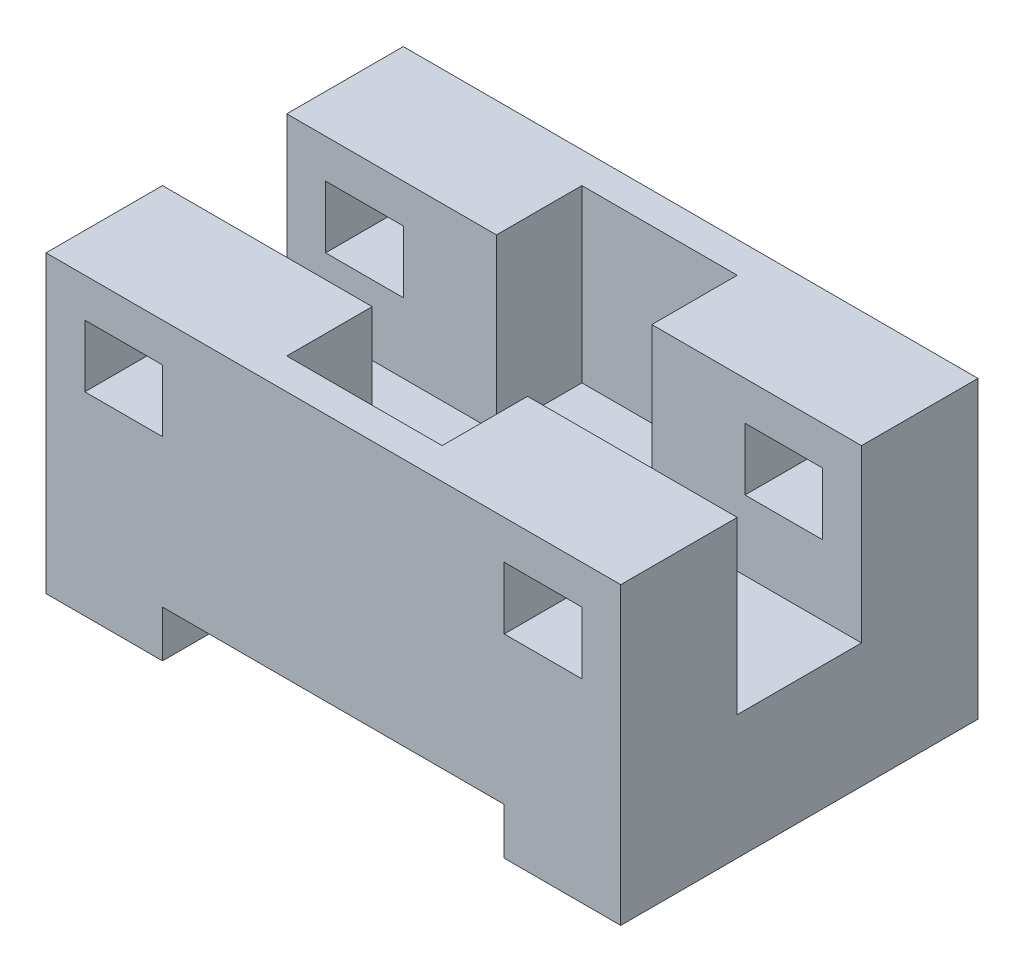
SolidWorks part; units mm, degrees
ref_plane "Alzado" through (0, 0, 0) normal (0, 0, 1) x (1, 0, 0)
ref_plane "Planta" through (0, 0, 0) normal (0, 1, 0) x (1, 0, 0)
ref_plane "Vista lateral" through (0, 0, 0) normal (1, 0, 0) x (0, 0, -1)
sketch "Croquis1" plane through (0, 0, 0) normal (0, 0, 1) x (1, 0, 0)
  line L0 (22, -6) -> (37, -6)
  line L1 (-37, 32) -> (37, 32)
  line L2 (-37, 32) -> (-37, -6)
  line L3 (-37, -6) -> (-22, -6)
  line L4 (37, 32) -> (37, -6)
  line L6 (-22, -6) -> (-22, 0)
  line L7 (-22, 0) -> (22, 0)
  line L8 (22, -6) -> (22, 0)
  point P8 (0, 0)
  point P9 (-4.2724, -15.6085)
  point P10 (23.9565, -10.0311)
  point P11 (-21.6729, -5.3379)
  point P12 (0, 0)
  dimension "D1" = 38
  dimension "D2" = 74
  dimension "D3" = 44
  dimension "D4" = 32
extrude "Saliente-Extruir1" add sketch "Croquis1" against normal blind 46
sketch "Croquis2" plane through (0, 32, 0) normal (0, 1, 0) x (1, 0, 0)
  line L0 (10, 15) -> (10, 4)
  line L1 (-37, 15) -> (-10, 15)
  line L2 (-37, 15) -> (-37, 31)
  line L3 (-37, 31) -> (-10, 31)
  line L4 (37, 15) -> (37, 31)
  line L5 (-10, 42) -> (10, 42)
  line L6 (-10, 42) -> (-10, 31)
  line L7 (-10, 4) -> (10, 4)
  line L8 (-37, 0) -> (37, 0)
  line L9 (37, 0) -> (37, 46)
  line L10 (37, 46) -> (-37, 46)
  line L11 (-37, 46) -> (-37, 0)
  line L12 (-37, 0) -> (37, 0)
  line L13 (37, 0) -> (37, 46)
  line L14 (37, 46) -> (-37, 46)
  line L15 (-37, 46) -> (-37, 0)
  line L16 (10, 42) -> (10, 31)
  line L17 (-10, 15) -> (-10, 4)
  line L18 (10, 31) -> (37, 31)
  line L19 (10, 15) -> (37, 15)
  line L20 (-37, 23) -> (37, 23) construction
  line L21 (0, 42) -> (0, 4) construction
  point P6 (37, 23)
  point P8 (37, 23)
  point P10 (-37, 23)
  point P11 (-37, 23)
  point P24 (19.215, 2.8562)
  point P25 (0, 23)
  point P26 (0, 23)
  point P27 (0, 0)
  point P28 (0, 4)
  point P29 (0, 0)
  point P30 (-3.7205, 38.7218)
  point P31 (0, 42)
  line M10 (37, 0) -> (37, 46)
  line M12 (-37, 46) -> (-37, 0)
  dimension "D1" = 0
  dimension "D2" = 16
  dimension "D3" = 20
  dimension "D4" = 38
extrude "Cortar-Extruir1" cut sketch "Croquis2" against normal blind 22 contours L0 L19 L18 L16 L5 L6 L3 L1 L17 L7 M10 M12
sketch "Croquis3" plane through (0, 0, 0) normal (0, 0, 1) x (1, 0, 0)
  line L0 (0, 0) -> (0, 32) construction
  line L1 (37, 32) -> (-37, 32) construction
  line L2 (-37, 32) -> (-37, -6) construction
  line L3 (-32, 27) -> (-22, 27)
  line L4 (-32, 27) -> (-32, 19)
  line L5 (-32, 19) -> (-22, 19)
  line L6 (-22, 27) -> (-22, 19)
  line L7 (32, 19) -> (22, 19)
  line L8 (22, 27) -> (22, 19)
  line L9 (32, 27) -> (22, 27)
  line L10 (32, 27) -> (32, 19)
  dimension "D1" = 10
  dimension "D2" = 8
  dimension "D3" = 5
  dimension "D4" = 5
extrude "Cortar-Extruir2" cut sketch "Croquis3" against normal through all
